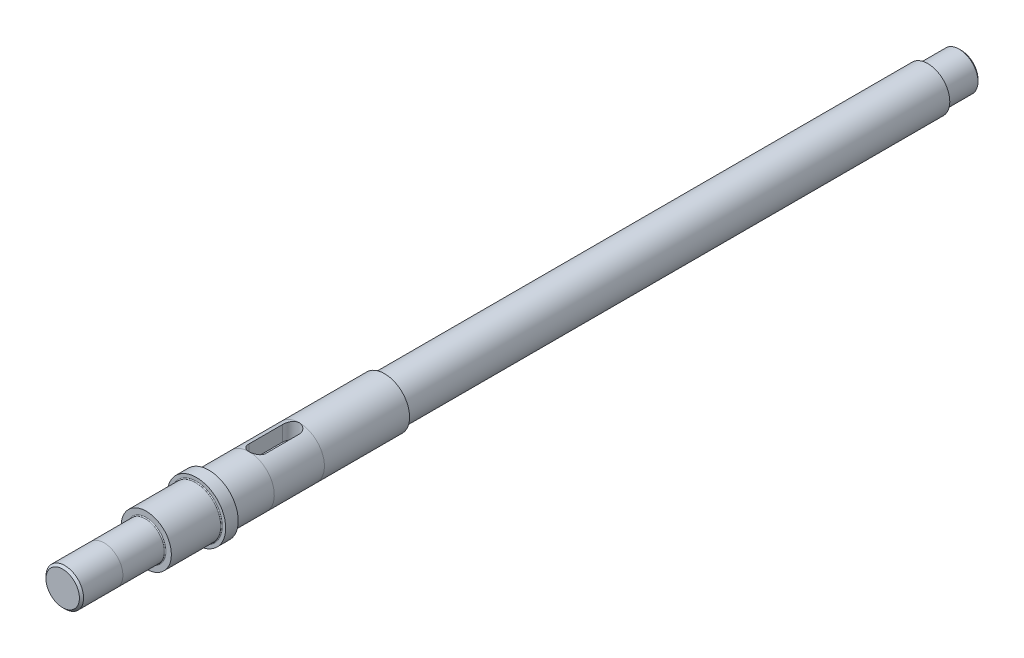
SolidWorks part; units mm, degrees
material "Сталь 45 ГОСТ 1050-2013"
ref_plane "Спереди" through (0, 0, 0) normal (0, 0, 1) x (1, 0, 0)
ref_plane "Сверху" through (0, 0, 0) normal (0, 1, 0) x (1, 0, 0)
ref_plane "Справа" through (0, 0, 0) normal (1, 0, 0) x (0, 0, -1)
sketch "Эскиз1" plane through (0, 0, 0) normal (0, 0, 1) x (1, 0, 0)
  circle A0 centre (0, 0) radius 5.25
extrude "Бобышка-Вытянуть1" add sketch "Эскиз1" along normal blind 130
sketch "Эскиз2" plane through (0, 0, 130) normal (0, 0, 1) x (1, 0, 0)
  circle A0 centre (0, 0) radius 6
extrude "Бобышка-Вытянуть2" add sketch "Эскиз2" along normal blind 42
sketch "Эскиз3" plane through (0, 0, 172) normal (0, 0, 1) x (1, 0, 0)
  circle A0 centre (0, 0) radius 7
extrude "Бобышка-Вытянуть3" add sketch "Эскиз3" along normal blind 3
sketch "Эскиз4" plane through (0, 0, 175) normal (0, 0, 1) x (1, 0, 0)
  circle A0 centre (0, 0) radius 6
extrude "Бобышка-Вытянуть4" add sketch "Эскиз4" along normal blind 12
sketch "Эскиз5" plane through (0, 0, 187) normal (0, 0, 1) x (1, 0, 0)
  circle A0 centre (0, 0) radius 4.5
extrude "Бобышка-Вытянуть5" add sketch "Эскиз5" along normal blind 8
sketch "Эскиз6" plane through (0, 0, 0) normal (0, 0, -1) x (-1, 0, 0)
  circle A0 centre (0, 0) radius 4.5
extrude "Бобышка-Вытянуть6" add sketch "Эскиз6" along normal blind 8
ref_plane "Плоскость1" through (0, 12, 0) normal (0, 1, 0) x (1, 0, 0)
sketch "Эскиз18" plane through (0, 12, 0) normal (0, 1, 0) x (1, 0, 0)
  line L0 (0, -206.7656) -> (0, 10.1519) construction
  line L1 (0, -160.3735) -> (0, -152.3735) construction
  line L8 (-2, -160.3735) -> (-2, -152.3735)
  line L9 (2, -160.3735) -> (2, -152.3735)
  arc A0 (-2, -160.3735) -> (2, -160.3735) centre (0, -160.3735) ccw
  arc A1 (2, -152.3735) -> (-2, -152.3735) centre (0, -152.3735) ccw
  point P3 (0, -157.4697)
  point P10 (0, -156.3735)
extrude "Вырез-Вытянуть1" cut sketch "Эскиз18" against normal blind 10
fillet "Скругление2" radius 0.2 1 edges at (4.5, 0, 0)
fillet "Скругление4" radius 0.2 1 edges at (6, 0, 175)
fillet "Скругление5" radius 0.2 1 edges at (4.5, 0, 187)
sketch "Эскиз19" plane through (0, 0, 195) normal (0, 0, 1) x (1, 0, 0)
  circle A0 centre (0, 0) radius 4.5
extrude "Бобышка-Вытянуть7" add sketch "Эскиз19" along normal blind 12
fillet "Скругление6" radius 0.2 1 edges at (5.25, 0, 130)
fillet "Скругление7" radius 0.2 1 edges at (6, 0, 172)
sketch "Эскиз20" plane through (0, 12, 0) normal (0, 1, 0) x (1, 0, 0)
  line L0 (-4.5, -197.1) -> (4.5, -197.1)
  line L1 (-4.5, -187.2) -> (-4.5, -207) construction
  line L2 (4.5, -207) -> (4.5, -187.2) construction
split line "Разделяющая линия3"
sketch "Эскиз21" plane through (0, 12, 0) normal (0, 1, 0) x (1, 0, 0)
  line L0 (-7.6417, -162.3735) -> (7.4388, -162.3735)
split line "Разделяющая линия4"
sketch "Эскиз22" plane through (0, 12, 0) normal (0, 1, 0) x (1, 0, 0)
  line L0 (-8.6317, -150.3735) -> (7.8592, -150.3735)
split line "Разделяющая линия5"
chamfer "Фаска1" distance 0.5 angle 45 2 edges at (-4.5, 0, -8) (4.5, 0, 207)
